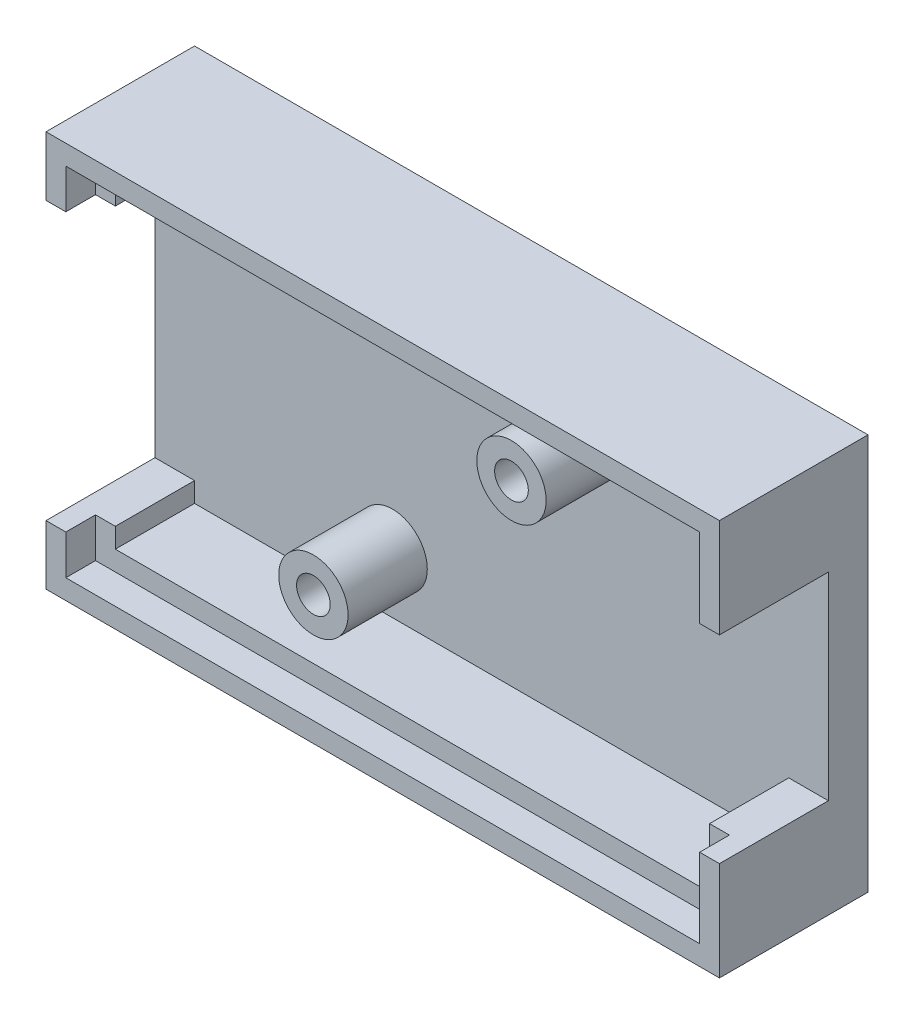
SolidWorks part; units mm, degrees
ref_plane "前视基准面" through (0, 0, 0) normal (0, 0, 1) x (1, 0, 0)
ref_plane "上视基准面" through (0, 0, 0) normal (0, 1, 0) x (1, 0, 0)
ref_plane "右视基准面" through (0, 0, 0) normal (1, 0, 0) x (0, 0, -1)
sketch "草图1" plane through (0, 0, 0) normal (0, 0, 1) x (1, 0, 0)
  line L1 (-17, 10) -> (17, 10)
  line L2 (-17, 10) -> (-17, -10)
  line L3 (-17, -10) -> (17, -10)
  line L4 (17, 10) -> (17, -10)
  line L5 (-17, 10) -> (17, -10) construction
  line L6 (-17, -10) -> (17, 10) construction
  point P1 (0, 0)
  dimension "D1" = 20
  dimension "D2" = 34
extrude "凸台-拉伸1" add sketch "草图1" along normal blind 7.5
sketch "草图2" plane through (0, 0, 7.5) normal (0, 0, 1) x (1, 0, 0)
  line L0 (-17, 10) -> (-17, -10) construction
  line L1 (-15, 8) -> (15, 8)
  line L2 (-15, 8) -> (-15, -8)
  line L3 (-15, -8) -> (15, -8)
  line L4 (15, 8) -> (15, -8)
  line L5 (17, 10) -> (-17, 10) construction
  line L6 (17, -10) -> (17, 10) construction
  line L7 (-17, -10) -> (17, -10) construction
  dimension "D1" = 2
  dimension "D2" = 2
  dimension "D3" = 2
  dimension "D4" = 2
extrude "切除-拉伸1" cut sketch "草图2" against normal blind 5.5
sketch "草图3" plane through (17, 0, 0) normal (1, 0, 0) x (0, 0, -1)
  line L0 (-7.5, -10) -> (-7.5, 10) construction
  line L1 (-7.5, 5) -> (-2, 5)
  line L2 (-7.5, 5) -> (-7.5, -5)
  line L3 (-7.5, -5) -> (-2, -5)
  line L4 (-2, 5) -> (-2, -5)
  line L5 (-7.5, 10) -> (0, 10) construction
  line L6 (-7.5, -10) -> (0, -10) construction
  dimension "D1" = 5
  dimension "D2" = 5
  dimension "D3" = 5.5
extrude "切除-拉伸2" cut sketch "草图3" against normal blind 2
sketch "草图4" plane through (-17, 0, 0) normal (-1, 0, 0) x (0, 0, 1)
  line L0 (7.5, 10) -> (7.5, -10) construction
  line L1 (7.5, 7) -> (2, 7)
  line L2 (7.5, 7) -> (7.5, -7)
  line L3 (7.5, -7) -> (2, -7)
  line L4 (2, 7) -> (2, -7)
  line L5 (7.5, 10) -> (0, 10) construction
  line L6 (7.5, -10) -> (0, -10) construction
  dimension "D1" = 3
  dimension "D2" = 3
  dimension "D3" = 5.5
extrude "切除-拉伸3" cut sketch "草图4" against normal blind 2
sketch "草图5" plane through (0, 0, 7.5) normal (0, 0, 1) x (1, 0, 0)
  line L1 (-15, 7) -> (-17, 7) construction
  line L2 (-16, 7) -> (-16, 9)
  line L3 (-16, 9) -> (16, 9)
  line L4 (16, 9) -> (16, 5)
  line L5 (15, 5) -> (17, 5) construction
  line L8 (15, 8) -> (-15, 8)
  line L10 (17, 10) -> (-17, 10) construction
  line L11 (-15, -7) -> (-15, -8)
  line L12 (-15, -8) -> (15, -8)
  line L15 (15, -5) -> (17, -5) construction
  line L16 (16, -5) -> (16, -9)
  line L17 (16, -9) -> (-16, -9)
  line L18 (-16, -9) -> (-16, -7)
  line L19 (-15, -7) -> (-17, -7) construction
  line L20 (-16, -7) -> (-15, -7)
  line L21 (-17, -10) -> (17, -10) construction
  line L22 (-15, 8) -> (-15, 7)
  line L23 (-15, 7) -> (-16, 7)
  line L24 (15, 8) -> (15, 5)
  line L25 (15, 5) -> (16, 5)
  line L26 (16, -5) -> (15, -5)
  line L27 (15, -5) -> (15, -8)
  point P0 (0, 0)
  dimension "D1" = 1
  dimension "D2" = 1
  dimension "D3" = 1
extrude "切除-拉伸4" cut sketch "草图5" against normal blind 1.5
sketch "草图6" plane through (0, 0, 2) normal (0, 0, 1) x (1, 0, 0)
  line L0 (-15, 8) -> (15, 8) construction
  line L1 (-15, -8) -> (15, -8) construction
  line L2 (-15, -8) -> (-15, -7) construction
  line L3 (15, 5) -> (15, 8) construction
  circle A0 centre (5, 5) radius 1.75
  circle A1 centre (-5, -5) radius 1.75
  dimension "D1" = 3.5
  dimension "D2" = 3.5
  dimension "D3" = 3
  dimension "D4" = 3
  dimension "D5" = 10
  dimension "D6" = 10
extrude "凸台-拉伸2" add sketch "草图6" along normal blind 4
sketch "草图7" plane through (0, 0, 6) normal (0, 0, 1) x (1, 0, 0)
  circle A0 centre (-5, -5) radius 0.85
  circle A1 centre (5, 5) radius 0.85
  dimension "D1" = 1.7
  dimension "D2" = 1.7
extrude "切除-拉伸5" cut sketch "草图7" against normal blind 3
